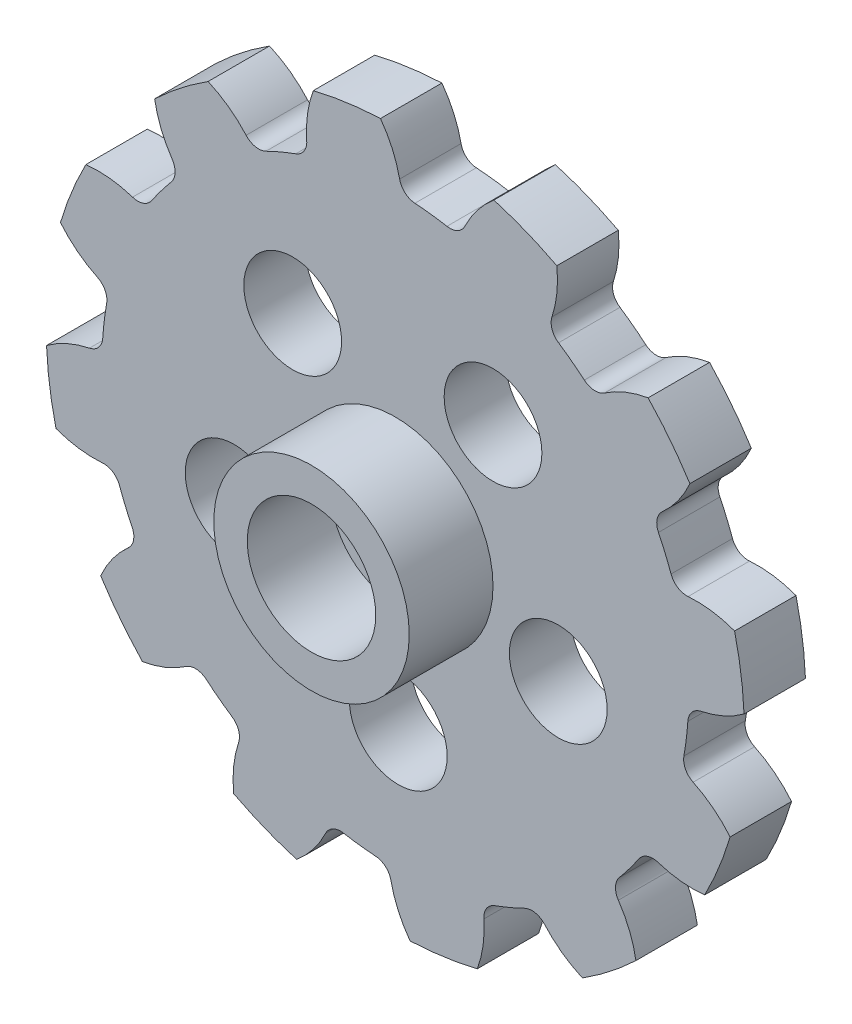
SolidWorks part; units mm, degrees
ref_plane "Alzado" through (0, 0, 0) normal (0, 0, 1) x (1, 0, 0)
ref_plane "Planta" through (0, 0, 0) normal (0, 1, 0) x (1, 0, 0)
ref_plane "Vista lateral" through (0, 0, 0) normal (1, 0, 0) x (0, 0, -1)
sketch "Croquis1" plane through (0, 0, 0) normal (0, 0, 1) x (1, 0, 0)
  line L0 (0, 0) -> (0, 1.1) construction
  line L1 (0, 0) -> (0, 1.1) construction
  line L2 (0, 0) -> (0.1906, 1.0834) construction
  circle A2 centre (0, 0) radius 1.1
  arc A6 (-0.5302, 12.4888) -> (4.7603, 11.5581) centre (0, 0) ccw
  arc A10 (4.7603, 11.5581) -> (-0.5302, 12.4888) centre (0, 0) ccw
  dimension "D1" = 25
  dimension "D4" = 2.2
extrude "Saliente-Extruir1" add sketch "Croquis1" along normal blind 2.2
sketch "Croquis2" plane through (0, 0, 2.2) normal (0, 0, 1) x (1, 0, 0)
  circle A0 centre (0, 0) radius 3.5
  circle A1 centre (0, 0) radius 2.3
  dimension "D1" = 1.2
  dimension "D2" = 7
extrude "Saliente-Extruir2" add sketch "Croquis2" along normal blind 3
sketch "Croquis3" plane through (0, 0, 0) normal (0, 0, -1) x (-1, 0, 0)
  circle A0 centre (0, 0) radius 2.25
  dimension "D1" = 4.5
extrude "Cortar-Extruir1" cut sketch "Croquis3" against normal blind 1
sketch "Croquis4" plane through (0, 0, 0) normal (0, 0, -1) x (-1, 0, 0)
  arc A0 (0.5302, 12.4888) -> (-3.5326, 11.9905) centre (0, 0) ccw
  arc A2 (-0.2222, 10.4976) -> (-2.3213, 10.2402) centre (0, 0) ccw
  arc A3 (0.5302, 12.4888) -> (-0.2222, 10.4976) centre (3.696, 10.1548) ccw
  arc A4 (-3.5326, 11.9905) -> (-2.3213, 10.2402) centre (-6.0405, 8.9606) cw
  dimension "D1" = 25
  dimension "D3" = 21
extrude "Cortar-Extruir2" cut sketch "Croquis4" along direction (0, 0, 1) on the side against the normal blind 10 contours A4 A2 A3 A0
fillet "Redondeo2" radius 0.6 2 edges at (0.2222, 10.4976, 1.1) (2.3213, 10.2402, 1.1)
pattern_circular "MatrizC3" count 12 every 30 about axis through (0, 0, 0) along (0, 0, 1) of "Cortar-Extruir2", "Redondeo2"
sketch "Croquis5" plane through (0, 0, 0) normal (0, 0, -1) x (-1, 0, 0)
  line L0 (0, 0) -> (0, 5) construction
  line L1 (0, 5) -> (-3.5, 5) construction
  circle A0 centre (-3.5, 5) radius 1.75
  circle A1 centre (3.6737, 4.8738) radius 1.75
  circle A2 centre (5.7705, -1.9878) radius 1.75
  circle A3 centre (-0.1074, -6.1023) radius 1.75
  circle A4 centre (-5.8368, -1.7836) radius 1.75
  point P16 (0, 0)
  dimension "D3" = 3.5
  dimension "D1" = 5
  dimension "D2" = 3.5
  dimension "D4" = 5
extrude "Cortar-Extruir3" cut sketch "Croquis5" along a picked direction on the side against the normal blind 10
